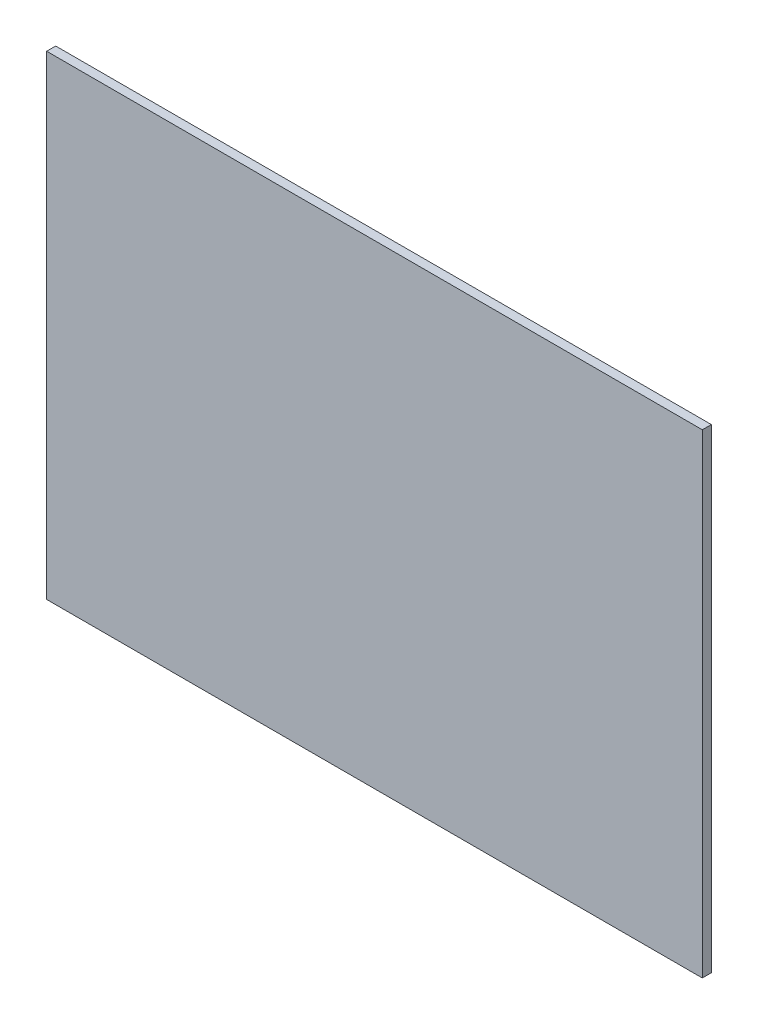
SolidWorks part; units mm, degrees
ref_plane "Front Plane" through (0, 0, 0) normal (0, 0, 1) x (1, 0, 0)
ref_plane "Top Plane" through (0, 0, 0) normal (0, 1, 0) x (1, 0, 0)
ref_plane "Right Plane" through (0, 0, 0) normal (1, 0, 0) x (0, 0, -1)
sketch "Sketch1" plane through (0, 0, 0) normal (0, 0, 1) x (1, 0, 0)
  line L0 (0, -105) -> (0, 0) construction
  line L1 (-145, 105) -> (145, 105)
  line L2 (-145, 105) -> (-145, -105)
  line L3 (-145, -105) -> (145, -105)
  line L4 (145, 105) -> (145, -105)
  line L5 (0, 0) -> (0, 105) construction
  dimension "D1" = 210
  dimension "D2" = 290
extrude "Boss-Extrude1" add sketch "Sketch1" along normal blind 4
